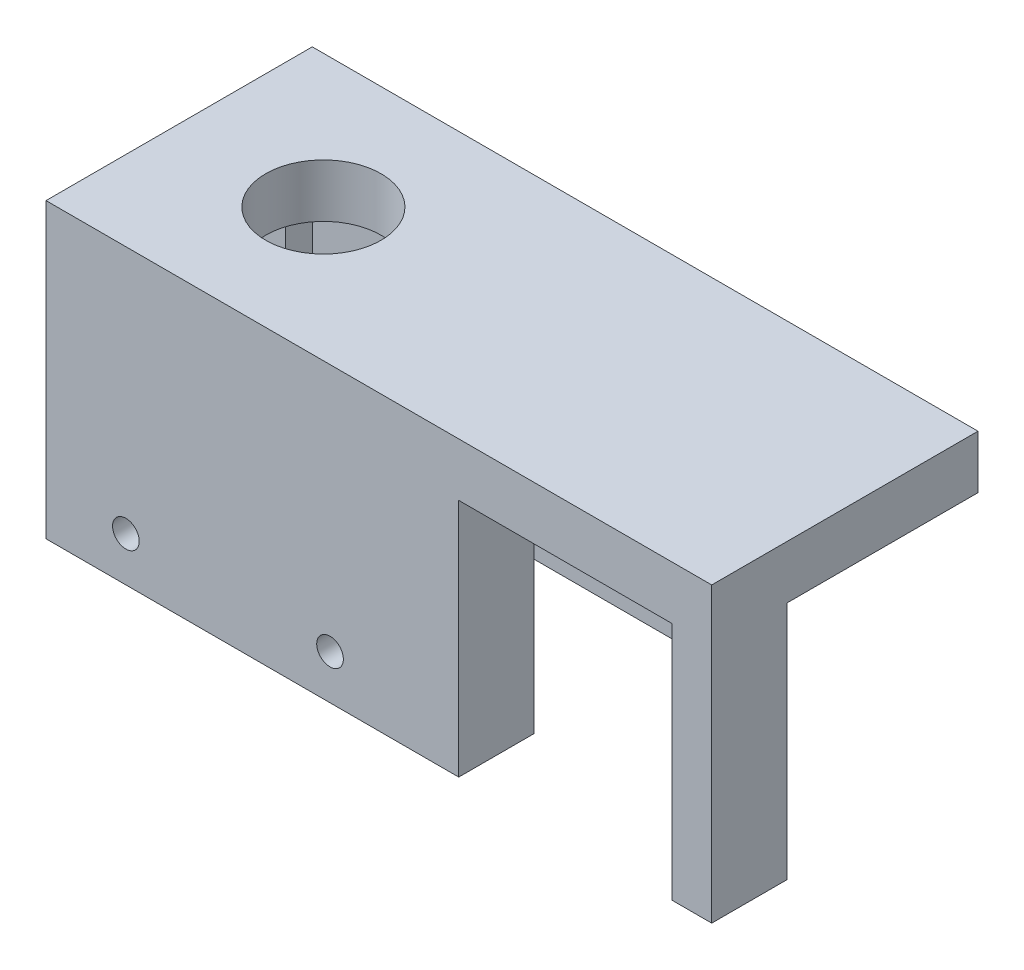
SolidWorks part; units mm, degrees
ref_plane "Front Plane" through (0, 0, 0) normal (0, 0, 1) x (1, 0, 0)
ref_plane "Top Plane" through (0, 0, 0) normal (0, 1, 0) x (1, 0, 0)
ref_plane "Right Plane" through (0, 0, 0) normal (1, 0, 0) x (0, 0, -1)
sketch "Sketch1" plane through (0, -4.342, 0) normal (0, -1, 0) x (1, 0, 0)
  line L0 (-40.9843, 28.2004) -> (-18.4843, 28.2004) construction
  line L1 (-11.5696, 28.2004) -> (-86.5696, 28.2004)
  line L2 (-11.5696, 28.2004) -> (-11.5696, -1.7996)
  line L3 (-11.5696, -1.7996) -> (-86.5696, -1.7996)
  line L4 (-86.5696, 28.2004) -> (-86.5696, -1.7996)
  dimension "D1" = 75
  dimension "D2" = 30
extrude "Boss-Extrude1" add sketch "Sketch1" along normal blind 6 contours L1 L4 L3 L2
sketch "Sketch2" plane through (0, -10.342, 0) normal (0, -1, 0) x (-1, 0, 0)
  line L1 (86.5696, 1.7996) -> (38.5696, 1.7996)
  line L2 (86.5696, 1.7996) -> (86.5696, -2.7004)
  line L3 (86.5696, -2.7004) -> (38.5696, -2.7004)
  line L4 (38.5696, 1.7996) -> (38.5696, -2.7004)
  line L5 (38.5696, 1.7996) -> (43.5696, 1.7996)
  line L6 (38.5696, 1.7996) -> (38.5696, -7.2004)
  line L7 (38.5696, -7.2004) -> (43.5696, -7.2004)
  line L8 (43.5696, 1.7996) -> (43.5696, -7.2004)
  line L9 (11.5696, -28.2004) -> (86.5696, -28.2004) construction
  line L10 (86.5696, 1.7996) -> (82.0696, 1.7996)
  line L11 (86.5696, 1.7996) -> (86.5696, -28.2004)
  line L12 (86.5696, -28.2004) -> (82.0696, -28.2004)
  line L13 (82.0696, 1.7996) -> (82.0696, -28.2004)
  line L14 (11.5696, -28.2004) -> (11.5696, 1.7996) construction
  line L15 (86.5696, -28.2004) -> (40.0696, -28.2004)
  line L16 (86.5696, -28.2004) -> (86.5696, -23.7004)
  line L17 (86.5696, -23.7004) -> (40.0696, -23.7004)
  line L18 (40.0696, -28.2004) -> (40.0696, -23.7004)
  line L19 (46.0696, -28.2004) -> (40.0696, -28.2004)
  line L20 (46.0696, -28.2004) -> (46.0696, -19.7004)
  line L21 (46.0696, -19.7004) -> (40.0696, -19.7004)
  line L22 (40.0696, -28.2004) -> (40.0696, -19.7004)
  line L24 (11.5696, -28.2004) -> (16.0696, -28.2004)
  line L25 (11.5696, -28.2004) -> (11.5696, -19.7004)
  line L26 (11.5696, -19.7004) -> (16.0696, -19.7004)
  line L27 (16.0696, -28.2004) -> (16.0696, -19.7004)
  dimension "D1" = 4.5
  dimension "D2" = 48
  dimension "D3" = 5
  dimension "D4" = 9
  dimension "D5" = 4.5
  dimension "D6" = 4.5
  dimension "D7" = 0
  dimension "D8" = 28.5
  dimension "D9" = 40.5
  dimension "D10" = 8.5
  dimension "D11" = 8.5
  dimension "D12" = 4.5
extrude "Boss-Extrude4" add sketch "Sketch2" along normal blind 27 contours L16 L15 L18 L17 | L2 L1 L4 L3 | L11 L10 L13 L12 | L6 L5 L8 L7 | L20 L19 L22 L21 | L25 L24 L27 L26
sketch "Sketch7" plane through (-38.5696, 0, 0) normal (1, 0, 0) x (0, 0, -1)
  line L1 (-7.2004, -37.342) -> (-2.7004, -37.342)
  line L2 (-7.2004, -37.342) -> (-7.2004, -22.342)
  line L3 (-7.2004, -22.342) -> (-2.7004, -22.342)
  line L4 (-2.7004, -37.342) -> (-2.7004, -22.342)
  dimension "D1" = 15
  dimension "D2" = 4.5
extrude "Cut-Extrude1" cut sketch "Sketch7" against normal blind 6
sketch "Sketch9" plane through (0, -4.342, 0) normal (0, 1, 0) x (1, 0, 0)
  line L1 (-86.5696, -28.2004) -> (-86.5696, 1.7996) construction
  line L2 (-11.5696, 1.7996) -> (-86.5696, 1.7996) construction
  circle A0 centre (-70.3196, -13.2004) radius 6.5
  dimension "D1" = 16.25
  dimension "D2" = 15
  dimension "D3" = 13
extrude "Cut-Extrude2" cut sketch "Sketch9" against normal blind 30
sketch "Sketch10" plane through (0, 0, 28.2004) normal (0, 0, 1) x (1, 0, 0)
  line L0 (-86.5696, -37.342) -> (-86.5696, -4.342) construction
  line L2 (-86.5696, -37.342) -> (-40.0696, -37.342) construction
  circle A0 centre (-77.5696, -32.342) radius 1.5
  dimension "D1" = 9
  dimension "D2" = 3
  dimension "D3" = 5
extrude "Cut-Extrude3" cut sketch "Sketch10" against normal blind 50
sketch "Sketch11" plane through (0, 0, 28.2004) normal (0, 0, 1) x (1, 0, 0)
  line L0 (-86.5696, -37.342) -> (-86.5696, -4.342) construction
  circle A0 centre (-54.5696, -32.342) radius 1.5
  circle A1 centre (-77.5696, -32.342) radius 1.5 construction
  dimension "D1" = 32
  dimension "D2" = 3
  dimension "D3" = 0
extrude "Cut-Extrude4" cut sketch "Sketch11" against normal blind 10
sketch "Sketch12" plane through (-86.5696, 0, 0) normal (-1, 0, 0) x (0, 0, 1)
  line L0 (-1.7996, -37.342) -> (28.2004, -37.342) construction
  line L1 (5.7004, -37.342) -> (20.7004, -37.342)
  line L2 (5.7004, -37.342) -> (5.7004, -11.342)
  line L3 (5.7004, -11.342) -> (20.7004, -11.342)
  line L4 (20.7004, -37.342) -> (20.7004, -11.342)
  line L5 (28.2004, -4.342) -> (-1.7996, -4.342) construction
  point P8 (13.2004, -4.342)
  dimension "D1" = 15
  dimension "D2" = 7.5
  dimension "D3" = 26
extrude "Cut-Extrude5" cut sketch "Sketch12" against normal blind 5
